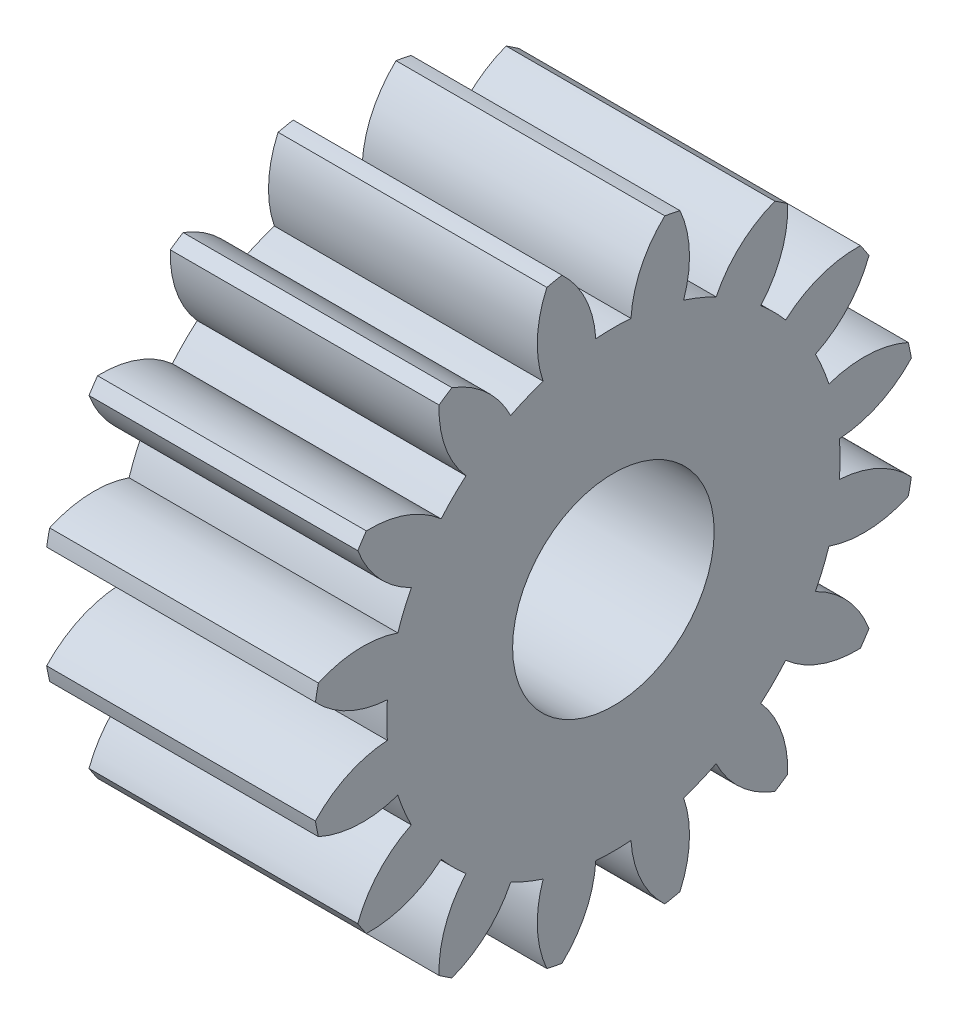
SolidWorks part; units mm, degrees
ref_plane "Plane1" through (0, 0, 0) normal (0, 0, 1) x (1, 0, 0)
ref_plane "Plane2" through (0, 0, 0) normal (0, 1, 0) x (1, 0, 0)
ref_plane "Plane3" through (0, 0, 0) normal (1, 0, 0) x (0, 0, -1)
sketch "HoldingSke" plane through (0, 0, 0) normal (0, 1, 0) x (1, 0, 0)
  line L0 (0, 0) -> (1.9225, -0.5513)
  line L1 (-15, 0) -> (100, 0) construction
  line L2 (0, 0) -> (-2.1039, 2.3779)
  line L3 (0, 0) -> (-11.863, 4.5341)
  line L4 (0, 0) -> (8.3015, 2.3804)
  line L5 (0, 0) -> (-46.8476, -17.4728)
  line L6 (0, 0) -> (-3.3159, -2.2372)
  line L7 (-2.1039, 2.3779) -> (8.6586, 51.2059)
  line L8 (-76.2, 54.61) -> (-75.7, 54.61)
  line L9 (-71.009, 38.7566) -> (-53.1078, 45.2721)
  line L10 (-76.2, 71.12) -> (104.1128, 71.12)
  line L11 (0, 0) -> (-4, 0)
  line L12 (-76.2, 101.6) -> (-76.181, 101.6)
  line L13 (24.9733, 27.94) -> (52.9518, 28.4284)
  line L14 (24.9733, 27.94) -> (24.9743, 27.94)
  line L15 (24.9733, 27.94) -> (100.4006, 29.5858)
  line L16 (-63.627, -0.5) -> (-12.827, -0.5)
  circle A0 centre (0, 0) radius 1.5
  circle A1 centre (0, 0) radius 3.374
  circle A2 centre (0, 0) radius 37.5
  circle A3 centre (0, 0) radius 1.5
  dimension "MHD" = 6.748
  dimension "Hub_dia" = 75
  dimension "Bore" = 3
  dimension "MBD" = 3
  dimension "Num_teeth" = 16
  dimension "Pitch" = 2
  dimension "Overall_len" = 50
  dimension "Show_teeth" = 16
  dimension "Thickness" = 4
  dimension "OAL" = 50.0001
  dimension "T_dim" = 0.5
  dimension "Ap" = 20
  dimension "H" = 19.05
  dimension "Pitch_radius" = 180.3128
  dimension "Width" = 4
  dimension "Backlash" = 0.019
  dimension "Addendum_fac" = 1
  dimension "Dedendum_fac" = 1.25
  dimension "Clearance_fac" = 0.25
  dimension "Dedendum_add" = 0.001
  dimension "Module" = 0.5
sketch "BasProSke" plane through (0, 0, 0) normal (0, 1, 0) x (1, 0, 0)
  line L0 (-10, 0) -> (60, 0) construction
  line L1 (0, 0) -> (0, 4.5)
  line L2 (0, 0) -> (4, 0)
  line L3 (4, 0) -> (4, 4.5)
  line L4 (4, 4.5) -> (0, 4.5)
  dimension "Thickness" = 4
  dimension "Diameter" = 9
revolve "Base-Revolve" add sketch "BasProSke" angle 360 about L0
sketch "TooCutSke" plane through (0, 0, 0) normal (1, 0, 0) x (0, 0, -1)
  line L1 (0, 0) -> (0, 107) construction
  line L2 (0, 0) -> (-0.4253, 3.9773) construction
  line L3 (0, 0) -> (-1.5544, 7.8146) construction
  line L4 (-0.4253, 3.9773) -> (-0.7772, 3.9073) construction
  arc A0 (0.2619, 3.3638) -> (-0.2619, 3.3638) centre (0, 0) ccw
  arc A1 (0.7886, 4.4562) -> (-0.7886, 4.4562) centre (0, 0) ccw
  circle A2 centre (0, 0) radius 4 construction
  circle A3 centre (0, 0) radius 3.7588 construction
  arc A4 (-0.2619, 3.3638) -> (-0.7886, 4.4562) centre (-1.8589, 3.2669) ccw
  arc A5 (0.7886, 4.4562) -> (0.2619, 3.3638) centre (1.8589, 3.2669) ccw
  dimension "Root_dia" = 6.748
  dimension "Overcut_dia" = 9.0508
  dimension "Pitch_dia" = 8
  dimension "Base_dia" = 7.5175
  dimension "Flank_rad" = 1.6
  dimension "Half_ang" = 11.25
  dimension "Half_CT" = 0.3588
extrude "ToothCut" cut sketch "TooCutSke" along normal through all
fillet "Breaks" [suppressed] radius 0.01
fillet "RootFillets" [suppressed] radius 0.126
pattern_circular "TeethCuts" count 16 every 22.5 about axis through (-10, 0, 0) along (1, 0, 0) of "ToothCut", "RootFillets", "Breaks"
sketch "HubNeaOneSke" plane through (0, 0, 0) normal (-1, 0, 0) x (0, 0, 1)
  circle A0 centre (0, 0) radius 3.374
  dimension "Diameter" = 6.748
extrude "HubNearOne" [suppressed] add sketch "HubNeaOneSke" along normal blind 46.0001
sketch "HubNeaBotSke" plane through (0, 0, 0) normal (-1, 0, 0) x (0, 0, 1)
  circle A0 centre (0, 0) radius 3.374
  dimension "Diameter" = 6.748
extrude "HubNearBoth" [suppressed] add sketch "HubNeaBotSke" along normal blind 23
ref_plane "FarPln" through (4, 0, 0) normal (1, 0, 0) x (0, 0, -1)
sketch "HubFarSke" plane through (4, 0, 0) normal (1, 0, 0) x (0, 0, -1)
  circle A0 centre (0, 0) radius 3.374
  dimension "Diameter" = 6.748
extrude "HubFar" [suppressed] add sketch "HubFarSke" along normal blind 23
sketch "BorSke" plane through (0, 0, 0) normal (1, 0, 0) x (0, 0, -1)
  circle A0 centre (0, 0) radius 1.5
  dimension "Diameter" = 3
extrude "Bore" cut sketch "BorSke" along normal mid plane 100.0001
sketch "KeySke" plane through (0, 0, 0) normal (1, 0, 0) x (0, 0, -1)
  line L0 (-0.6, 0) -> (-0.6, 2)
  line L1 (-0.6, 2) -> (0.6, 2)
  line L2 (0.6, 2) -> (0.6, 0)
  line L3 (0, 0) -> (0, 34) construction
  line L4 (-0.6, 0) -> (0.6, 0)
  dimension "Offset" = 2
  dimension "Width" = 1.2
extrude "Keyway" [suppressed] cut sketch "KeySke" along normal mid plane 100.0001
pattern_circular "Keyway2" [suppressed] count 2 every 90 about axis through (-10, 0, 0) along (1, 0, 0)
equation "' \"Module@HoldingSke\" = 6.35"
equation "' \"Num_teeth@HoldingSke\" = 12"
equation "' \"Ap@HoldingSke\" =  20"
equation "' \"Ap@HoldingSke\" = 20"
equation "' \"Width@HoldingSke\" = 0.5 * 25.4"
equation "' \"Hub_dia@HoldingSke\"= 1 * 25.4"
equation "' \"Hub_dia@HoldingSke\" = 1 * 25.4"
equation "' \"Overall_len@HoldingSke\" = 1.0 * 25.4"
equation "' \"Bore@HoldingSke\" = 0.75 * 25.4"
equation "' \"T_dim@HoldingSke\" = 0.1 * 25.4"
equation "' \"Width@KeySke\" = 0.25 * 25.4"
equation "' \"Show_teeth@HoldingSke\" = 13"
equation "' \"Backlash@HoldingSke\" = 0.009 * 25.4"
equation "' \"Addendum_fac@HoldingSke\" = 1.0"
equation "' \"Dedendum_fac@HoldingSke\" = 1.25"
equation "' \"Dedendum_add@HoldingSke\" = 0.00005 * 25.4"
equation "' \"Clearance_fac@HoldingSke\" = 0.25"
equation "\"Pitch@HoldingSke\" = 1 / \"Module@HoldingSke\""
equation "\"Overcut_dia@TooCutSke\" = (\"Num_teeth@HoldingSke\" + 2 * \"Addendum_fac@HoldingSke\") / \"Pitch@HoldingSke\" + 0.002 * 25.4"
equation "\"Pitch_dia@TooCutSke\" = \"Num_teeth@HoldingSke\" / \"Pitch@HoldingSke\""
equation "\"Base_dia@TooCutSke\" = \"Num_teeth@HoldingSke\" / \"Pitch@HoldingSke\" * cos((\"Ap@HoldingSke\"  * 3.14159265 / 180))"
equation "\"Root_dia@TooCutSke\" = (\"Num_teeth@HoldingSke\" + 2) / \"Pitch@HoldingSke\" - 2 * (\"Addendum_fac@HoldingSke\" + \"Dedendum_fac@HoldingSke\") / \"Pitch@HoldingSke\" - \"Dedendum_add@HoldingSke\" * 2"
equation "\"Half_ang@TooCutSke\" = 180 / \"Num_teeth@HoldingSke\""
equation "\"Half_CT@TooCutSke\" = \"Num_teeth@HoldingSke\" / \"Pitch@HoldingSke\" * sin((3.14159265 / 2 / \"Num_teeth@HoldingSke\")) / 2 - 7 * \"Backlash@HoldingSke\" / 4"
equation "\"Flank_rad@TooCutSke\" = \"Num_teeth@HoldingSke\" / \"Pitch@HoldingSke\" / 5"
equation "\"Radius@RootFillets\" = \"Clearance_fac@HoldingSke\" / \"Pitch@HoldingSke\" + \"Dedendum_add@HoldingSke\""
equation "\"Break_rad@Breaks\" = 0.02 / \"Pitch@HoldingSke\""
equation "\"Thickness@HoldingSke\" = \"Width@HoldingSke\""
equation "\"OAL@HoldingSke\" = \"Thickness@HoldingSke\""
equation "\"MHD@HoldingSke\" = (\"Num_teeth@HoldingSke\" + 2) / \"Pitch@HoldingSke\" - 2 * (\"Addendum_fac@HoldingSke\" + \"Dedendum_fac@HoldingSke\")  / \"Pitch@HoldingSke\" - \"Dedendum_add@HoldingSke\" * 2"
equation "\"MBD@HoldingSke\" = (\"Num_teeth@HoldingSke\" + 2) / \"Pitch@HoldingSke\" - 2 * (\"Addendum_fac@HoldingSke\" + \"Dedendum_fac@HoldingSke\")  / \"Pitch@HoldingSke\" - \"Dedendum_add@HoldingSke\" * 2 - 0.002 * 25.4"
equation "\"MHD@HoldingSke\" = ((sgn( \"MHD@HoldingSke\" - \"Hub_dia@HoldingSke\" )-1)*( \"MHD@HoldingSke\" - \"Hub_dia@HoldingSke\" ))/-2+ \"Hub_dia@HoldingSke\""
equation "\"MBD@HoldingSke\" = ((sgn( \"MBD@HoldingSke\" - \"Bore@HoldingSke\" )-1)*( \"MBD@HoldingSke\" - \"Bore@HoldingSke\" ))/-2+ \"Bore@HoldingSke\""
equation "\"OAL@HoldingSke\" = ((sgn( \"OAL@HoldingSke\" - \"Overall_len@HoldingSke\" )+1)*( \"OAL@HoldingSke\" - \"Overall_len@HoldingSke\" ))/2 + \"Overall_len@HoldingSke\" + 0.000002 * 25.4"
equation "\"Num_teeth@TeethCuts\" = int( \"Show_teeth@HoldingSke\" ) + 1"
equation "\"Num_teeth@TeethCuts\" = ((sgn( \"Num_teeth@TeethCuts\" - \"Num_teeth@HoldingSke\" )-1)*( \"Num_teeth@TeethCuts\" - \"Num_teeth@HoldingSke\" ))/-2+ \"Num_teeth@HoldingSke\""
equation "\"Num_teeth@TeethCuts\" = ((sgn( \"Num_teeth@TeethCuts\" - 2.0)+1)*( \"Num_teeth@TeethCuts\" - 2.0))/2 +2.0"
equation "\"Angle@TeethCuts\" = 360.0 / \"Num_teeth@HoldingSke\""
equation "\"Diameter@BasProSke\" = (\"Num_teeth@HoldingSke\" + 2 * \"Addendum_fac@HoldingSke\") / \"Pitch@HoldingSke\""
equation "\"Thickness@BasProSke\"  = \"Thickness@HoldingSke\""
equation "' \"Fillet_rad@BasProSke\" =  \"Thickness@HoldingSke\" * 0.05"
equation "' \"Fillet_rad@BasProSke\" = \"Thickness@HoldingSke\" * 0.05"
equation "\"MHD@HoldingSke\" = ((sgn( \"MHD@HoldingSke\" - \"Root_dia@TooCutSke\" )-1)*( \"MHD@HoldingSke\" - \"Root_dia@TooCutSke\" ))/-2+ \"Root_dia@TooCutSke\""
equation "\"Diameter@HubNeaOneSke\" = \"MHD@HoldingSke\""
equation "\"Length@HubNearOne\" = \"OAL@HoldingSke\" - \"Thickness@BasProSke\""
equation "\"Diameter@HubNeaBotSke\" = \"MHD@HoldingSke\""
equation "\"Length@HubNearBoth\" = ( \"OAL@HoldingSke\" - \"Thickness@BasProSke\" ) / 2.0"
equation "\"Thickness@FarPln\" = \"Thickness@BasProSke\""
equation "\"Diameter@HubFarSke\" = \"MHD@HoldingSke\""
equation "\"Length@HubFar\" = ( \"OAL@HoldingSke\" - \"Thickness@BasProSke\" ) / 2.0"
equation "\"Diameter@BorSke\" = \"MBD@HoldingSke\""
equation "\"D1@Bore\" = \"OAL@HoldingSke\" * 2.0"
equation "\"D1@Keyway\" = \"OAL@HoldingSke\" * 2.0"
equation "\"Offset@KeySke\" = \"T_dim@HoldingSke\" + \"MBD@HoldingSke\" / 2.0"
